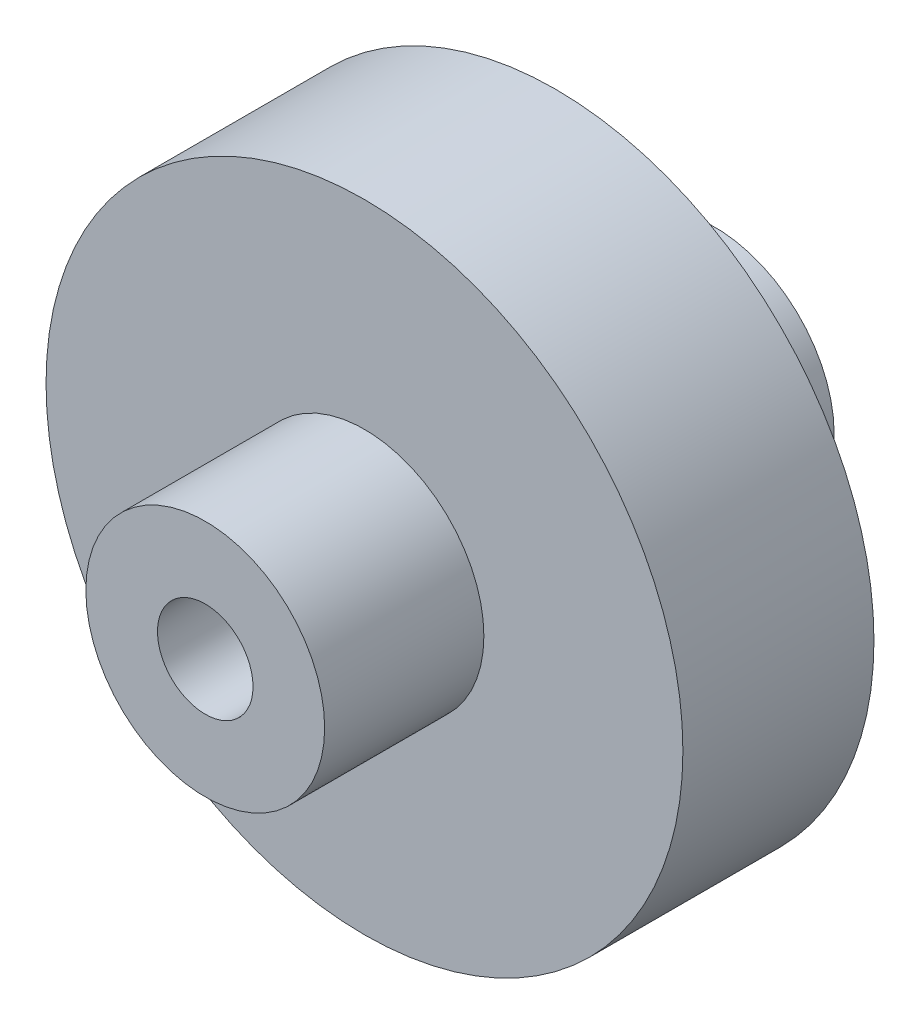
SolidWorks part; units mm, degrees
ref_plane "Front Plane" through (0, 0, 0) normal (0, 0, 1) x (1, 0, 0)
ref_plane "Top Plane" through (0, 0, 0) normal (0, 1, 0) x (1, 0, 0)
ref_plane "Right Plane" through (0, 0, 0) normal (1, 0, 0) x (0, 0, -1)
sketch "Sketch1" plane through (0, 0, 0) normal (0, 0, 1) x (1, 0, 0)
  circle A0 centre (0, 0) radius 20
  dimension "D1" = 40
extrude "Boss-Extrude1" add sketch "Sketch1" along normal blind 32
sketch "Sketch2" plane through (0, 0, 32) normal (0, 0, 1) x (1, 0, 0)
  circle A0 centre (0, 0) radius 3
  dimension "D1" = 6
extrude "Cut-Extrude1" cut sketch "Sketch2" against normal blind 32
sketch "Sketch3" plane through (0, 0, 32) normal (0, 0, 1) x (1, 0, 0)
  circle A0 centre (0, 0) radius 20
  circle A1 centre (0, 0) radius 7.5
  dimension "D1" = 15
extrude "Cut-Extrude2" cut sketch "Sketch3" against normal blind 10
sketch "Sketch4" plane through (0, 0, 0) normal (0, 0, -1) x (-1, 0, 0)
  circle A0 centre (0, 0) radius 20
  circle A1 centre (0, 0) radius 7.5
  dimension "D1" = 15
extrude "Cut-Extrude3" cut sketch "Sketch4" against normal blind 10
sketch "Sketch6" plane through (0, 0, 32) normal (0, 0, 1) x (1, 0, 0)
  line L1 (-0.7939, 2.5427) -> (1.2061, 2.5427)
  line L2 (-0.7939, 2.5427) -> (-0.7939, 7.3762)
  line L3 (-0.7939, 7.3762) -> (1.2061, 7.3762)
  line L4 (1.2061, 2.5427) -> (1.2061, 7.3762)
  dimension "D1" = 2
  dimension "D2" = 2
extrude "Cut-Extrude4" cut sketch "Sketch6" against normal blind 2 from offset 7
